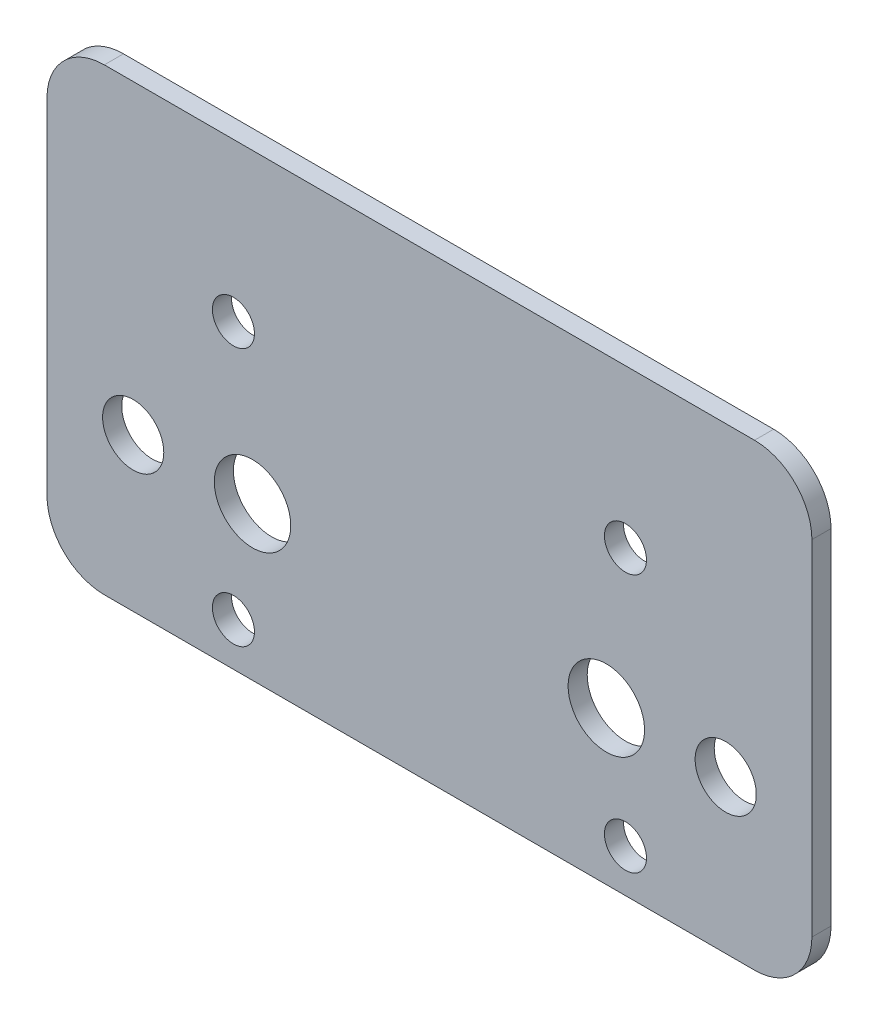
SolidWorks part; units mm, degrees
ref_plane "Front Plane" through (0, 0, 0) normal (0, 0, 1) x (1, 0, 0)
ref_plane "Top Plane" through (0, 0, 0) normal (0, 1, 0) x (1, 0, 0)
ref_plane "Right Plane" through (0, 0, 0) normal (1, 0, 0) x (0, 0, -1)
sketch "Sketch1" plane through (0, 0, 0) normal (0, 0, 1) x (1, 0, 0)
  line L0 (0, 0) -> (0, -8.0708) construction
  line L1 (20, -12) -> (-20, -12)
  line L2 (20, -12) -> (20, 12)
  line L3 (20, 12) -> (-20, 12)
  line L4 (-20, -12) -> (-20, 12)
  line L5 (20, -12) -> (-20, 12) construction
  line L6 (20, 12) -> (-20, -12) construction
  line L7 (0, -4) -> (14.7109, -4) construction
  circle A0 centre (-15.4919, -4) radius 1.6
  circle A1 centre (15.4919, -4) radius 1.6
  circle A2 centre (0, -4) radius 8 construction
  circle A3 centre (0, -4) radius 8 construction
  point P0 (0, 0)
  point P6 (-15.4919, -4)
  dimension "D4" = 3.2
  dimension "D1" = 24
  dimension "D2" = 40
  dimension "D3" = 16
extrude "Boss-Extrude1" add sketch "Sketch1" along normal blind 1
fillet "Fillet1" radius 3 4 edges at (-20, 12, 0.5) (-20, -12, 0.5) (20, -12, 0.5) (20, 12, 0.5)
sketch "Sketch2" plane through (0, 0, 0) normal (0, 0, -1) x (-1, 0, 0)
  arc A0 (-9.25, -5.5) -> (-9.25, -2.5) centre (-9.25, -4) ccw construction
  arc A1 (-9.25, -2.5) -> (-9.25, -5.5) centre (-9.25, -4) ccw construction
  arc A2 (9.25, -2.5) -> (9.25, -5.5) centre (9.25, -4) ccw construction
  arc A3 (9.25, -5.5) -> (9.25, -2.5) centre (9.25, -4) ccw construction
  arc A4 (10.25, 4.85) -> (10.25, 2.65) centre (10.25, 3.75) ccw construction
  arc A5 (10.25, 2.65) -> (10.25, 4.85) centre (10.25, 3.75) ccw construction
  arc A6 (10.25, -8.65) -> (10.25, -10.85) centre (10.25, -9.75) ccw construction
  arc A7 (10.25, -10.85) -> (10.25, -8.65) centre (10.25, -9.75) ccw construction
  arc A8 (-10.25, 4.85) -> (-10.25, 2.65) centre (-10.25, 3.75) ccw construction
  arc A9 (-10.25, 2.65) -> (-10.25, 4.85) centre (-10.25, 3.75) ccw construction
  arc A10 (-10.25, -8.65) -> (-10.25, -10.85) centre (-10.25, -9.75) ccw construction
  arc A11 (-10.25, -10.85) -> (-10.25, -8.65) centre (-10.25, -9.75) ccw construction
  arc A12 (-9.25, -5.5) -> (-9.25, -2.5) centre (-9.25, -4) ccw construction
  arc A13 (-9.25, -2.5) -> (-9.25, -5.5) centre (-9.25, -4) ccw construction
  arc A14 (9.25, -2.5) -> (9.25, -5.5) centre (9.25, -4) ccw construction
  arc A15 (9.25, -5.5) -> (9.25, -2.5) centre (9.25, -4) ccw construction
  arc A16 (10.25, 4.85) -> (10.25, 2.65) centre (10.25, 3.75) ccw
  arc A17 (10.25, 2.65) -> (10.25, 4.85) centre (10.25, 3.75) ccw
  arc A18 (10.25, -8.65) -> (10.25, -10.85) centre (10.25, -9.75) ccw
  arc A19 (10.25, -10.85) -> (10.25, -8.65) centre (10.25, -9.75) ccw
  arc A20 (-10.25, 4.85) -> (-10.25, 2.65) centre (-10.25, 3.75) ccw
  arc A21 (-10.25, 2.65) -> (-10.25, 4.85) centre (-10.25, 3.75) ccw
  arc A22 (-10.25, -8.65) -> (-10.25, -10.85) centre (-10.25, -9.75) ccw
  arc A23 (-10.25, -10.85) -> (-10.25, -8.65) centre (-10.25, -9.75) ccw
  arc A24 (-9.25, -6) -> (-9.25, -2) centre (-9.25, -4) ccw
  arc A25 (-9.25, -2) -> (-9.25, -6) centre (-9.25, -4) ccw
  arc A26 (9.25, -2) -> (9.25, -6) centre (9.25, -4) ccw
  arc A27 (9.25, -6) -> (9.25, -2) centre (9.25, -4) ccw
  dimension "D1" = 0.5
extrude "Cut-Extrude1" cut sketch "Sketch2" against normal through all
